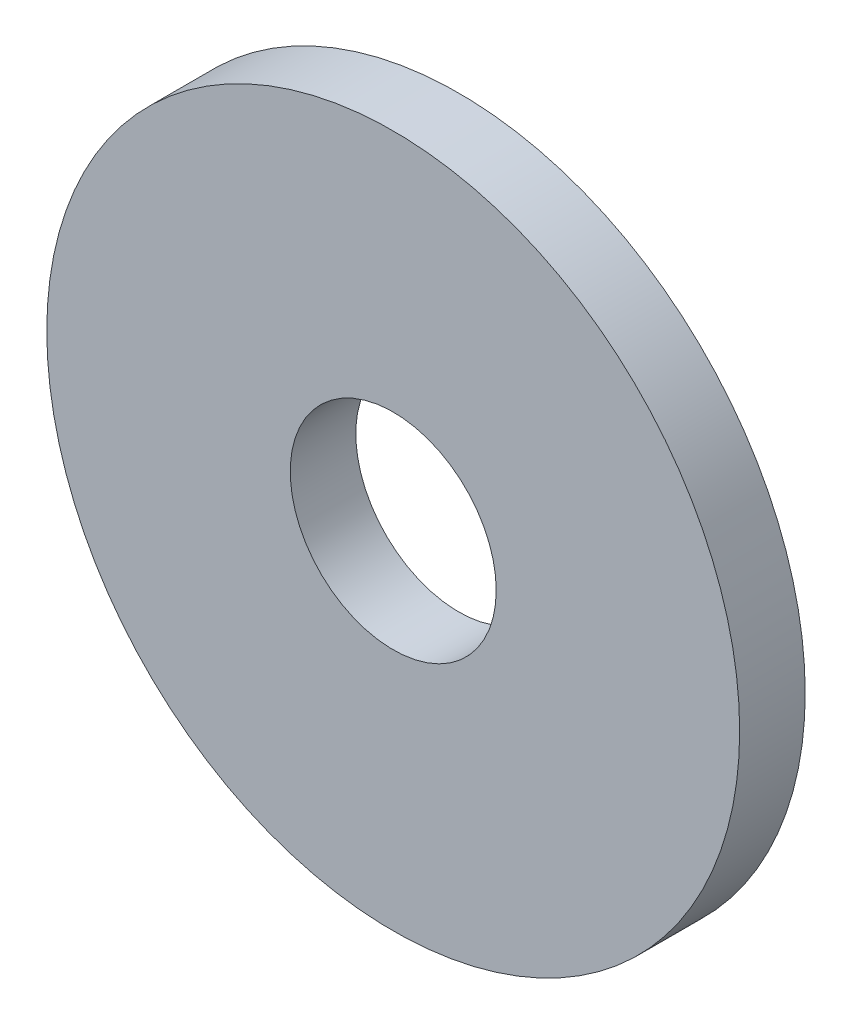
SolidWorks part; units mm, degrees
ref_plane "Front Plane" through (0, 0, 0) normal (0, 0, 1) x (1, 0, 0)
ref_plane "Top Plane" through (0, 0, 0) normal (0, 1, 0) x (1, 0, 0)
ref_plane "Right Plane" through (0, 0, 0) normal (1, 0, 0) x (0, 0, -1)
sketch "Sketch1" plane through (0, 0, 0) normal (0, 0, 1) x (1, 0, 0)
  circle A0 centre (0, 0) radius 37
  circle A1 centre (0, 0) radius 11
  dimension "D1" = 74
  dimension "D2" = 22
extrude "Boss-Extrude1" add sketch "Sketch1" along normal blind 7
